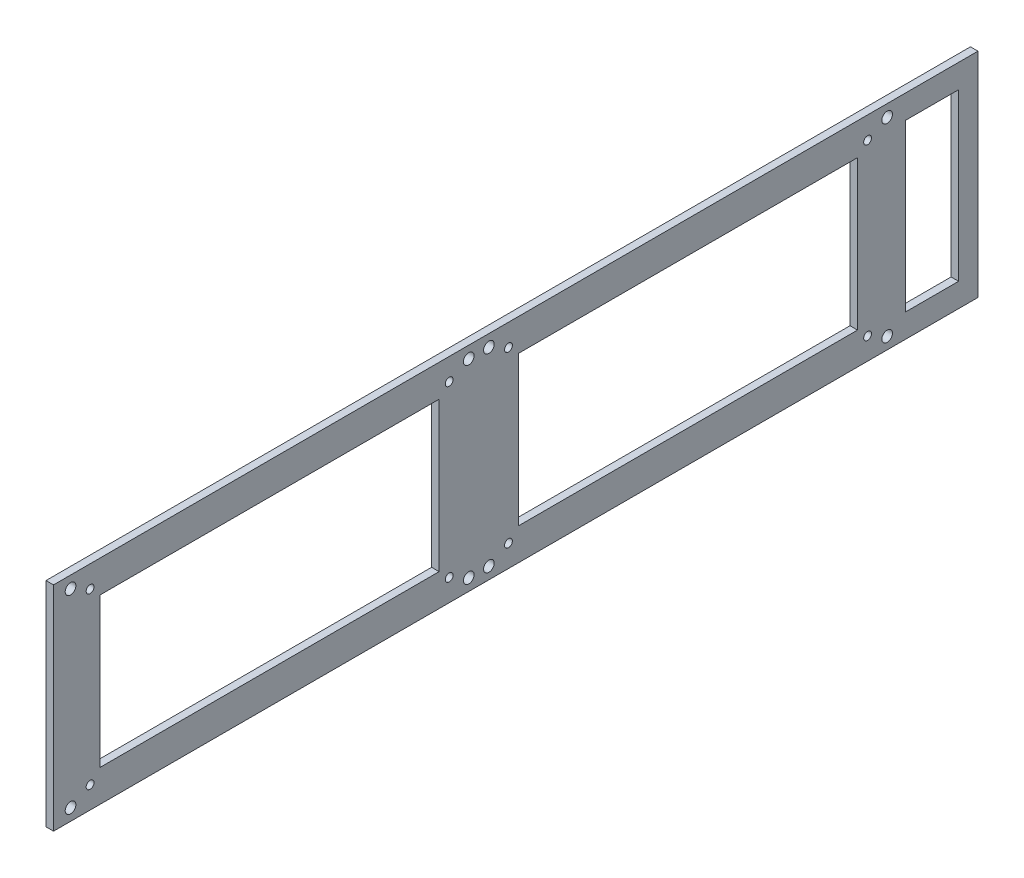
SolidWorks part; units mm, degrees
ref_plane "Front Plane" through (0, 0, 0) normal (0, 0, 1) x (1, 0, 0)
ref_plane "Top Plane" through (0, 0, 0) normal (0, 1, 0) x (1, 0, 0)
ref_plane "Right Plane" through (0, 0, 0) normal (1, 0, 0) x (0, 0, -1)
sketch "Sketch1" plane through (0, 0, 0) normal (1, 0, 0) x (0, 0, -1)
  line L1 (-195, -45) -> (195, -45)
  line L2 (-195, -45) -> (-195, 45)
  line L3 (-195, 45) -> (195, 45)
  line L4 (195, -45) -> (195, 45)
  line L5 (-195, -45) -> (195, 45) construction
  line L6 (-195, 45) -> (195, -45) construction
  point P0 (0, 0)
  dimension "D1" = 90
  dimension "D2" = 390
extrude "Boss-Extrude1" add sketch "Sketch1" along normal blind 3.175
sketch "Sketch2" plane through (3.175, 0, 0) normal (1, 0, 0) x (0, 0, -1)
  line L0 (1.175, -31.5) -> (144.175, -31.5)
  line L1 (-175.325, -31.5) -> (-32.325, -31.5)
  line L2 (-175.325, -31.5) -> (-175.325, 31.5)
  line L3 (-175.325, 31.5) -> (-32.325, 31.5)
  line L4 (-32.325, -31.5) -> (-32.325, 31.5)
  line L5 (-175.325, -31.5) -> (-32.325, 31.5) construction
  line L6 (-175.325, 31.5) -> (-32.325, -31.5) construction
  line L7 (-195, 45) -> (-195, -45) construction
  line L8 (1.175, -31.5) -> (1.175, 31.5)
  line L9 (1.175, 31.5) -> (144.175, 31.5)
  line L10 (144.175, -31.5) -> (144.175, 31.5)
  line L11 (1.175, -31.5) -> (144.175, 31.5) construction
  line L12 (1.175, 31.5) -> (144.175, -31.5) construction
  point P0 (-103.825, 0)
  point P5 (72.675, 0)
  dimension "D1" = 63
  dimension "D2" = 143
  dimension "D3" = 91.175
  dimension "D4" = 2
extrude "Cut-Extrude1" cut sketch "Sketch2" against normal blind 3.175
hole_wizard "M4x0.7 Tapped Hole1" positions "Sketch3" profile "Sketch5" tap size "M4x0.7" standard "ANSI Metric" end condition through all
sketch "Sketch3" plane through (3.175, 0, 0) normal (1, 0, 0) x (0, 0, -1)
  line L1 (-179.575, -35.75) -> (-28.075, -35.75)
  line L2 (-179.575, -35.75) -> (-179.575, 35.75)
  line L3 (-179.575, 35.75) -> (-28.075, 35.75)
  line L4 (-28.075, -35.75) -> (-28.075, 35.75)
  line L5 (-179.575, -35.75) -> (-28.075, 35.75) construction
  line L6 (-179.575, 35.75) -> (-28.075, -35.75) construction
  line L8 (-3.075, -35.75) -> (148.425, -35.75)
  line L9 (-3.075, -35.75) -> (-3.075, 35.75)
  line L10 (-3.075, 35.75) -> (148.425, 35.75)
  line L11 (148.425, -35.75) -> (148.425, 35.75)
  line L12 (-3.075, -35.75) -> (148.425, 35.75) construction
  line L13 (-3.075, 35.75) -> (148.425, -35.75) construction
  line L14 (-195, 45) -> (-195, -45) construction
  point P1 (-103.825, 0)
  point P2 (-28.075, 35.75)
  point P101 (-179.575, -35.75)
  point P102 (-179.575, 35.75)
  point P103 (-28.075, -35.75)
  point P104 (72.675, 0)
  point P105 (148.425, 35.75)
  point P166 (-3.075, -35.75)
  point P167 (-3.075, 35.75)
  point P168 (148.425, -35.75)
  dimension "D1" = 91.175
  dimension "D2" = 176.5
  dimension "D3" = 71.5
  dimension "D4" = 151.5
  dimension "D5" = 151.5
sketch "Sketch5" plane through (3.175, 0, 103.825) normal (0, 1, 0) x (0, 0, -1)
  line L0 (0, 0) -> (0, 3.175)
  line L1 (0, 3.175) -> (1.65, 3.175)
  line L2 (1.65, 3.175) -> (1.65, 0)
  line L5 (1.65, 0) -> (0, 0)
  line L11 (0, -6.35) -> (0, 107.95) construction
  dimension "Thru Tap Drill Dia." = 3.3
  dimension "Thru Tap Drill Depth" = 3.175
sketch "Sketch6" plane through (3.175, 0, 0) normal (1, 0, 0) x (0, 0, -1)
  line L0 (195, -45) -> (195, 45) construction
  line L1 (164.35, -35) -> (186.825, -35)
  line L2 (164.35, -35) -> (164.35, 35)
  line L3 (164.35, 35) -> (186.825, 35)
  line L4 (186.825, -35) -> (186.825, 35)
  line L5 (164.35, -35) -> (186.825, 35) construction
  line L6 (164.35, 35) -> (186.825, -35) construction
  line L7 (195, 45) -> (-195, 45) construction
  point P0 (175.5875, 0)
  dimension "D1" = 30.65
  dimension "D2" = 8.175
  dimension "D3" = 10
extrude "Cut-Extrude2" cut sketch "Sketch6" against normal blind 3.175
hole_wizard "M4 Clearance Hole2" positions "Sketch7" profile "Sketch8" hole size "M4" standard "ANSI Metric" end condition through all
sketch "Sketch7" plane through (3.175, 0, 0) normal (1, 0, 0) x (0, 0, -1)
  line L1 (-187.825, -40) -> (-19.825, -40)
  line L2 (-187.825, -40) -> (-187.825, 40)
  line L3 (-187.825, 40) -> (-19.825, 40)
  line L4 (-19.825, -40) -> (-19.825, 40)
  line L5 (-187.825, -40) -> (-19.825, 40) construction
  line L6 (-187.825, 40) -> (-19.825, -40) construction
  line L9 (-11.325, -40) -> (156.675, -40)
  line L10 (-11.325, -40) -> (-11.325, 40)
  line L11 (-11.325, 40) -> (156.675, 40)
  line L12 (156.675, -40) -> (156.675, 40)
  line L13 (-11.325, -40) -> (156.675, 40) construction
  line L14 (-11.325, 40) -> (156.675, -40) construction
  point P1 (-103.825, 0)
  point P2 (-19.825, 40)
  point P105 (-187.825, -40)
  point P106 (-187.825, 40)
  point P107 (-19.825, -40)
  point P175 (72.675, 0)
  point P176 (156.675, 40)
  point P243 (-11.325, -40)
  point P244 (-11.325, 40)
  point P245 (156.675, -40)
  dimension "D1" = 80
  dimension "D2" = 168
  dimension "D3" = 168
sketch "Sketch8" plane through (3.175, 0, 103.825) normal (0, 1, 0) x (0, 0, -1)
  line L0 (0, 0) -> (0, 3.175)
  line L1 (0, 3.175) -> (2.25, 3.175)
  line L2 (2.25, 3.175) -> (2.25, 0)
  line L5 (2.25, 0) -> (0, 0)
  line L11 (0, -6.35) -> (0, 107.95) construction
  dimension "Thru Hole Dia." = 4.5
  dimension "Thru Hole Depth" = 3.175
